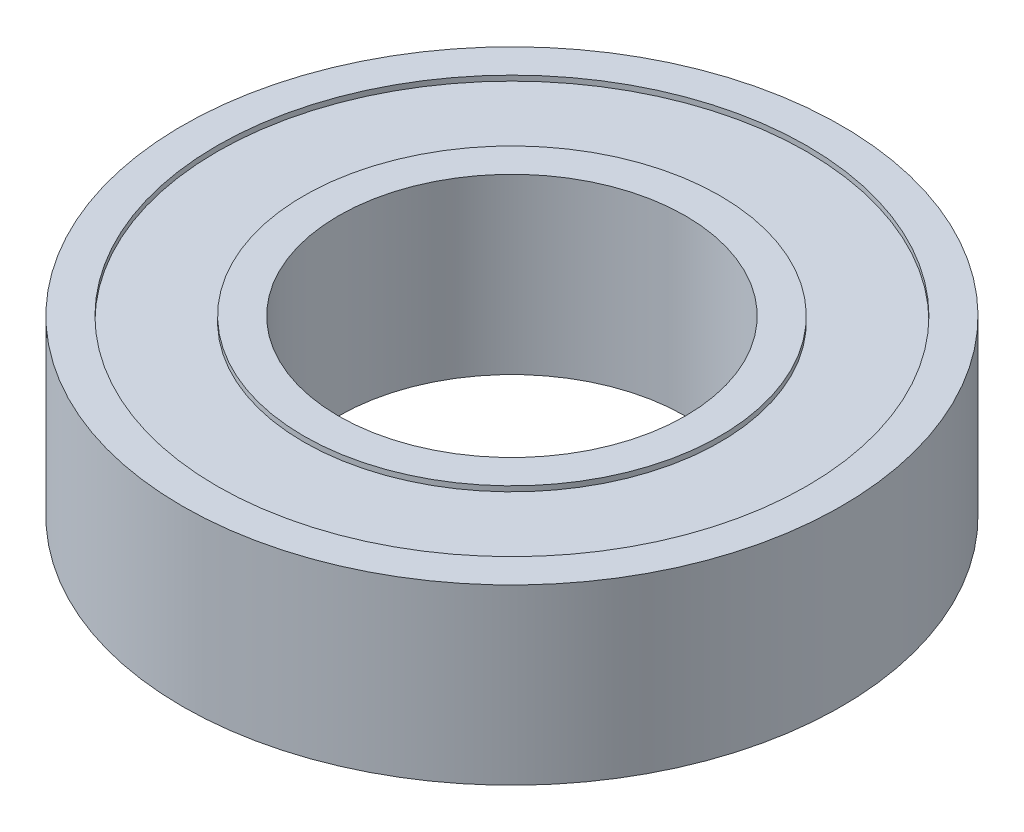
SolidWorks part; units mm, degrees
ref_plane "Front Plane" through (0, 0, 0) normal (0, 0, 1) x (1, 0, 0)
ref_plane "Top Plane" through (0, 0, 0) normal (0, 1, 0) x (1, 0, 0)
ref_plane "Right Plane" through (0, 0, 0) normal (1, 0, 0) x (0, 0, -1)
sketch "Sketch1" plane through (0, 0, 0) normal (0, 1, 0) x (1, 0, 0)
  circle A0 centre (0, 0) radius 9.5
  circle A1 centre (0, 0) radius 5
  dimension "D1" = 19
  dimension "D2" = 10
extrude "Boss-Extrude1" add sketch "Sketch1" along normal mid plane 5
sketch "Sketch2" plane through (0, 2.5, 0) normal (0, 1, 0) x (1, 0, 0)
  circle A2 centre (0, 0) radius 8.5
  circle A3 centre (0, 0) radius 8.5
  circle A5 centre (0, 0) radius 6
  circle A6 centre (0, 0) radius 6
  dimension "D1" = 1
  dimension "D2" = 1
extrude "Cut-Extrude1" cut sketch "Sketch2" against normal blind 0.15
mirror "Mirror1" about plane through (0, 0, 0) normal (0, 1, 0) of "Cut-Extrude1"
